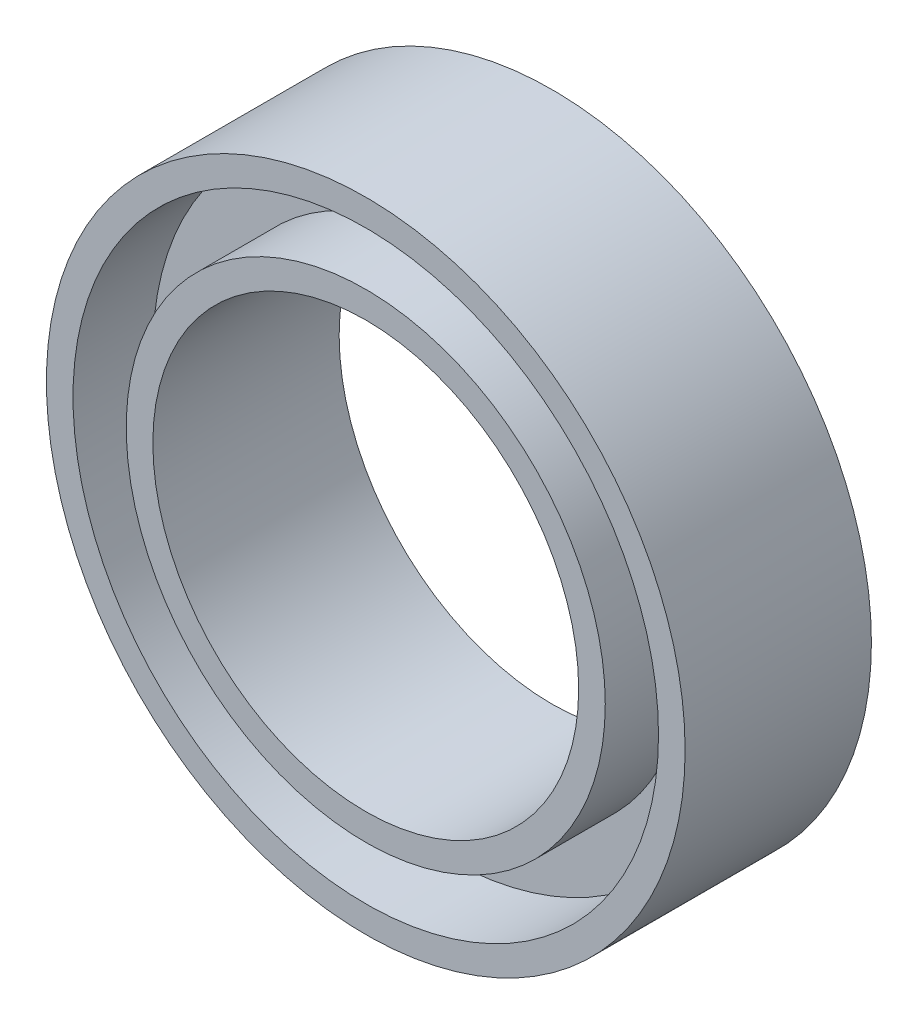
SolidWorks part; units mm, degrees
ref_plane "前视基准面" through (0, 0, 0) normal (0, 0, 1) x (1, 0, 0)
ref_plane "上视基准面" through (0, 0, 0) normal (0, 1, 0) x (1, 0, 0)
ref_plane "右视基准面" through (0, 0, 0) normal (1, 0, 0) x (0, 0, -1)
sketch "草图1" plane through (0, 0, 0) normal (0, 0, 1) x (1, 0, 0)
  circle A0 centre (0, 0) radius 4
  circle A1 centre (0, 0) radius 6
extrude "凸台-拉伸1" add sketch "草图1" along normal blind 3.5
sketch "草图2" plane through (0, 0, 3.5) normal (0, 0, 1) x (1, 0, 0)
  circle A0 centre (0, 0) radius 4.5
  circle A1 centre (0, 0) radius 5.5
extrude "切除-拉伸1" cut sketch "草图2" against normal blind 1.5
sketch "草图3" plane through (0, 0, 0) normal (0, 0, -1) x (-1, 0, 0)
  circle A0 centre (0, 0) radius 4.5 construction
  circle A3 centre (0, 0) radius 5.5
  circle A4 centre (0, 0) radius 5.5
  circle A5 centre (0, 0) radius 4.5
  dimension "D2" = 0
extrude "切除-拉伸2" cut sketch "草图3" against normal blind 1.5
